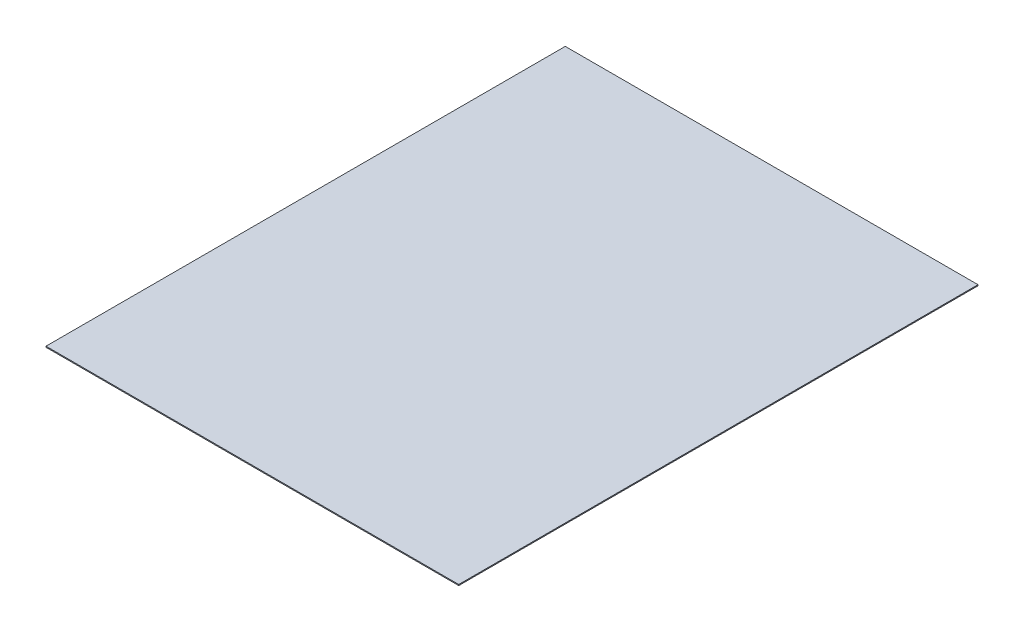
SolidWorks part; units mm, degrees
ref_plane "Front Plane" through (0, 0, 0) normal (0, 0, 1) x (1, 0, 0)
ref_plane "Top Plane" through (0, 0, 0) normal (0, 1, 0) x (1, 0, 0)
ref_plane "Right Plane" through (0, 0, 0) normal (1, 0, 0) x (0, 0, -1)
other "Configuration Table"
sketch "Sketch1" plane through (0, 0, 0) normal (0, 0, 1) x (1, 0, 0)
  line L1 (40, 1152) -> (660, 1152)
  line L2 (40, 1152) -> (40, 1153.5)
  line L3 (40, 1153.5) -> (660, 1153.5)
  line L4 (660, 1152) -> (660, 1153.5)
extrude "PRESS_uc_rafi_raf_1" add sketch "Sketch1" against normal blind 780 from offset 20 separate body
